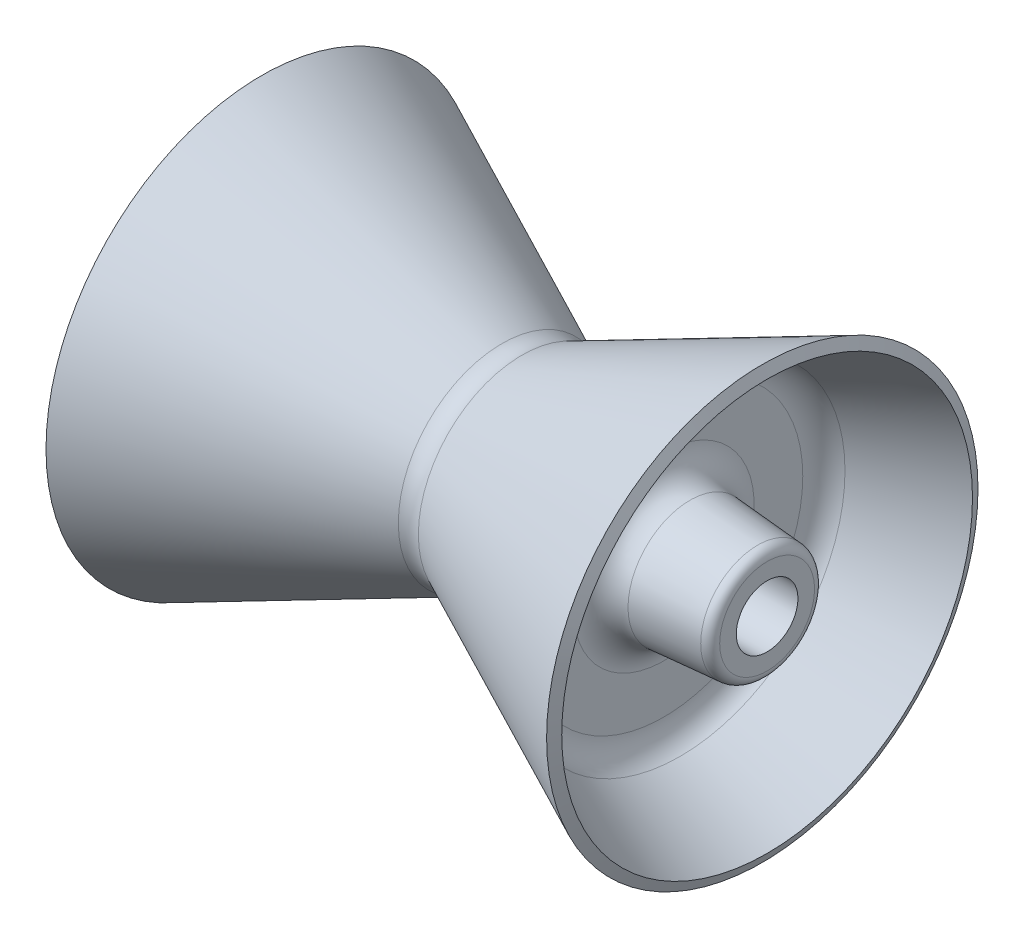
SolidWorks part; units mm, degrees
ref_plane "Front Plane" through (0, 0, 0) normal (0, 0, 1) x (1, 0, 0)
ref_plane "Top Plane" through (0, 0, 0) normal (0, 1, 0) x (1, 0, 0)
ref_plane "Right Plane" through (0, 0, 0) normal (1, 0, 0) x (0, 0, -1)
sketch "Sketch1" plane through (0, 0, 0) normal (0, 0, 1) x (1, 0, 0)
  line L0 (-518.6372, 0) -> (536.4233, 0) construction
  line L1 (0, 390.6468) -> (0, -390.6468) construction
  line L2 (130, 32.5) -> (269.015, 32.5)
  line L3 (269.015, 32.5) -> (269.015, 50)
  line L4 (259.015, 60) -> (187.7341, 65.3992)
  line L5 (130, 32.5) -> (130, 104.67)
  line L6 (160, 95.3136) -> (160, 146.6377)
  line L7 (177.3215, 173.8269) -> (269.015, 216.5843)
  line L8 (269.015, 216.5843) -> (263.9436, 227.46)
  line L9 (263.9436, 227.46) -> (10.5655, 109.3078)
  line L10 (10.5655, 96.0673) -> (87.3215, 131.8592)
  line L11 (-10.5655, 96.0673) -> (-87.3215, 131.8592)
  line L12 (-263.9436, 227.46) -> (-10.5655, 109.3078)
  line L13 (-269.015, 216.5843) -> (-263.9436, 227.46)
  line L14 (-177.3215, 173.8269) -> (-269.015, 216.5843)
  line L15 (-160, 95.3136) -> (-160, 146.6377)
  line L16 (-130, 32.5) -> (-130, 104.67)
  line L17 (-259.015, 60) -> (-187.7341, 65.3992)
  line L18 (-269.015, 32.5) -> (-269.015, 50)
  line L19 (-130, 32.5) -> (-269.015, 32.5)
  arc A0 (269.015, 50) -> (259.015, 60) centre (259.015, 50) ccw
  arc A1 (187.7341, 65.3992) -> (160, 95.3136) centre (190, 95.3136) cw
  arc A2 (160, 146.6377) -> (177.3215, 173.8269) centre (190, 146.6377) cw
  arc A3 (130, 104.67) -> (87.3215, 131.8592) centre (100, 104.67) ccw
  arc A4 (-130, 104.67) -> (-87.3215, 131.8592) centre (-100, 104.67) cw
  arc A5 (-160, 146.6377) -> (-177.3215, 173.8269) centre (-190, 146.6377) ccw
  arc A6 (-187.7341, 65.3992) -> (-160, 95.3136) centre (-190, 95.3136) ccw
  arc A7 (-269.015, 50) -> (-259.015, 60) centre (-259.015, 50) cw
  arc A8 (10.5655, 109.3078) -> (-10.5655, 109.3078) centre (0, 131.9655) cw
  arc A9 (10.5655, 96.0673) -> (-10.5655, 96.0673) centre (0, 118.725) cw
  point P20 (160, 67.5)
  point P41 (-160, 67.5)
  point P43 (0, 104.3811)
  point P46 (0, 91.1406)
  dimension "D6" = 67.5
  dimension "D7" = 227.46
  dimension "D2" = 139.015
  dimension "D10" = 12
  dimension "D4" = 10
  dimension "D12" = 30
  dimension "D14" = 25
  dimension "D1" = 130
  dimension "D3" = 32.5
  dimension "D5" = 60
  dimension "D8" = 30
  dimension "D9" = 65
  dimension "D11" = 269.015
  dimension "D13" = 12
revolve "Revolve1" add sketch "Sketch1" angle 360 about L0
